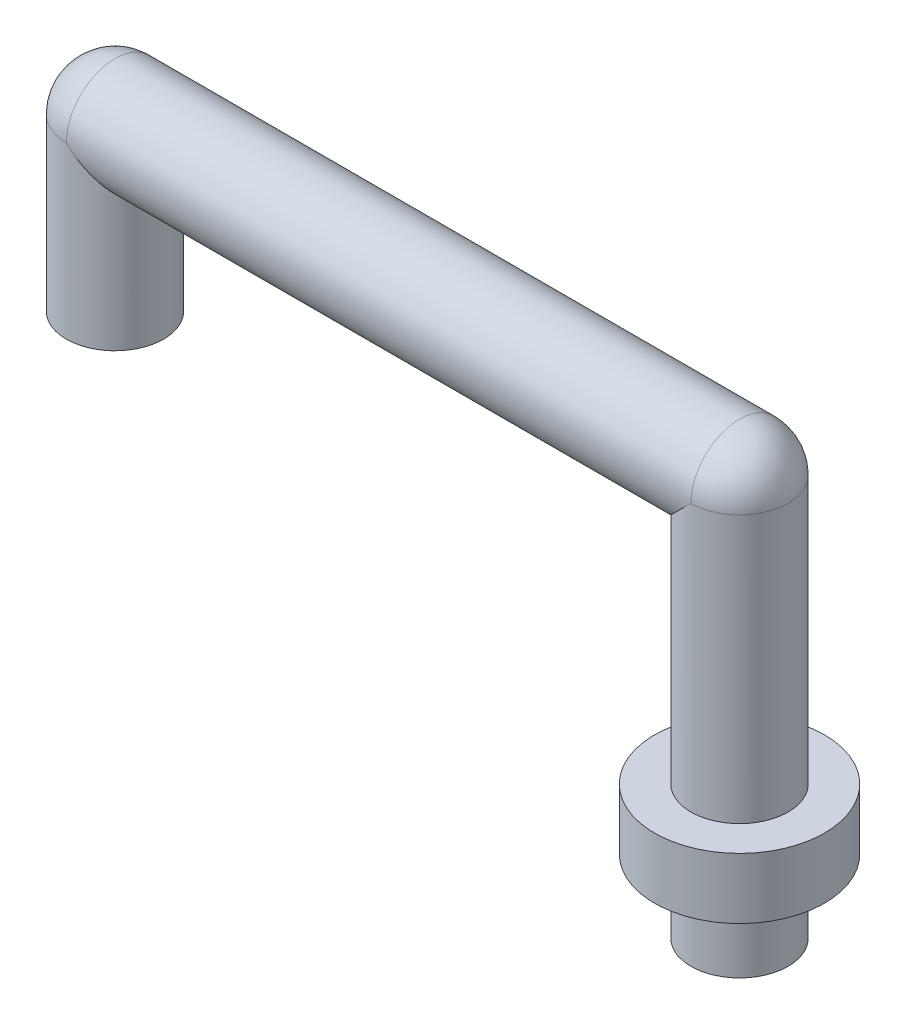
SolidWorks part; units mm, degrees
ref_plane "Front Plane" through (0, 0, 0) normal (0, 0, 1) x (1, 0, 0)
ref_plane "Top Plane" through (0, 0, 0) normal (0, 1, 0) x (1, 0, 0)
ref_plane "Right Plane" through (0, 0, 0) normal (1, 0, 0) x (0, 0, -1)
sketch "Sketch2" plane through (0, 0, 0) normal (0, 1, 0) x (-1, 0, 0)
  circle A0 centre (0, 0) radius 5.08
  dimension "D1" = 10.16
extrude "Boss-Extrude2" add sketch "Sketch2" along normal blind 41.91
sketch "Sketch3" plane through (0, 0, 0) normal (0, 0, 1) x (1, 0, 0)
  line L1 (0, 0) -> (0, 7.62) construction
  line L4 (0, 7.62) -> (0, 13.97)
  line L7 (0, 7.62) -> (-8.89, 7.62)
  line L8 (-8.89, 7.62) -> (-8.89, 13.97)
  line L9 (-8.89, 13.97) -> (0, 13.97)
  dimension "D1" = 6.35
  dimension "D2" = 8.89
  dimension "D3" = 7.62
revolve "Revolve1" add sketch "Sketch3" angle 360 about L1
sketch "Sketch4" plane through (0, 41.91, 0) normal (0, 1, 0) x (1, 0, 0)
  line L0 (0, 5.08) -> (0, -5.08) construction
  line L1 (-5.08, 0) -> (5.08, 0) construction
  line L2 (0, 5.08) -> (-65.278, 5.08)
  line L3 (-65.278, 5.08) -> (-65.278, 0)
  line L4 (-65.278, 0) -> (5.08, 0)
  arc A2 (5.08, 0) -> (0, 5.08) centre (0, 0) ccw
  dimension "D1" = 10.16
  dimension "D2" = 65.278
revolve "Revolve2" add sketch "Sketch4" angle 360 about L4
sketch "Sketch5" plane through (-65.278, 0, 0) normal (-1, 0, 0) x (0, 0, 1)
  line L0 (0, 46.99) -> (0, 24.13)
  line L1 (-5.08, 41.91) -> (5.08, 41.91) construction
  line L2 (-5.08, 41.91) -> (-5.08, 24.13)
  line L3 (-5.08, 24.13) -> (0, 24.13)
  arc A0 (0, 46.99) -> (-5.08, 41.91) centre (0, 41.91) ccw
  circle A1 centre (0, 41.91) radius 5.08 construction
  dimension "D1" = 22.86
revolve "Revolve3" add sketch "Sketch5" angle 360 about L0
